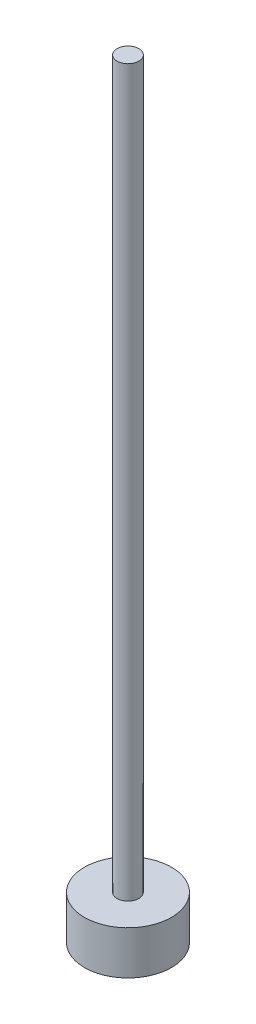
SolidWorks part; units mm, degrees
ref_plane "Front Plane" through (0, 0, 0) normal (0, 0, 1) x (1, 0, 0)
ref_plane "Top Plane" through (0, 0, 0) normal (0, 1, 0) x (1, 0, 0)
ref_plane "Right Plane" through (0, 0, 0) normal (1, 0, 0) x (0, 0, -1)
sketch "Sketch1" plane through (0, 0, 0) normal (0, 1, 0) x (1, 0, 0)
  circle A0 centre (0, 0) radius 3
  dimension "D1" = 6
extrude "Boss-Extrude1" add sketch "Sketch1" along normal blind 3
sketch "Sketch2" plane through (0, 3, 0) normal (0, 1, 0) x (1, 0, 0)
  circle A0 centre (0, 0) radius 0.75
  dimension "D1" = 1.5
extrude "Boss-Extrude2" add sketch "Sketch2" along normal blind 50
